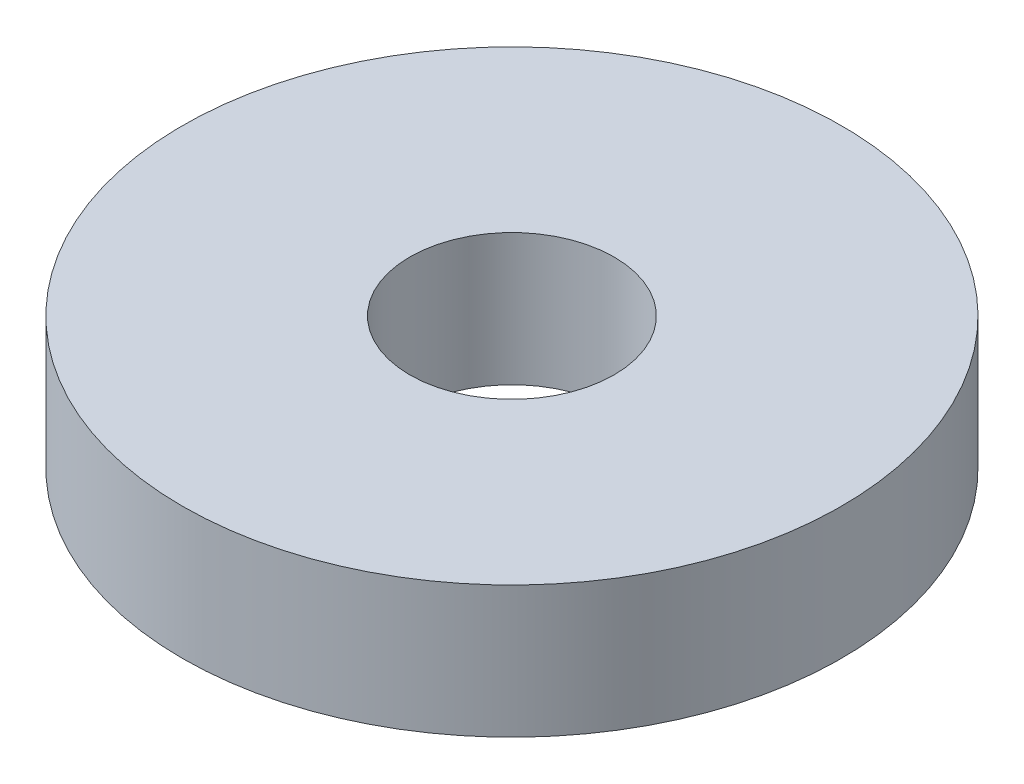
SolidWorks part; units mm, degrees
ref_plane "前视基准面" through (0, 0, 0) normal (0, 0, 1) x (1, 0, 0)
ref_plane "上视基准面" through (0, 0, 0) normal (0, 1, 0) x (1, 0, 0)
ref_plane "右视基准面" through (0, 0, 0) normal (1, 0, 0) x (0, 0, -1)
other "Configuration Table"
sketch "草图1" plane through (0, 0, 0) normal (0, 1, 0) x (1, 0, 0)
  circle A0 centre (0, 0) radius 1.55
  circle A1 centre (0, 0) radius 5
  dimension "D1" = 3.1
  dimension "D2" = 10
extrude "凸台-拉伸1" add sketch "草图1" along normal blind 2
